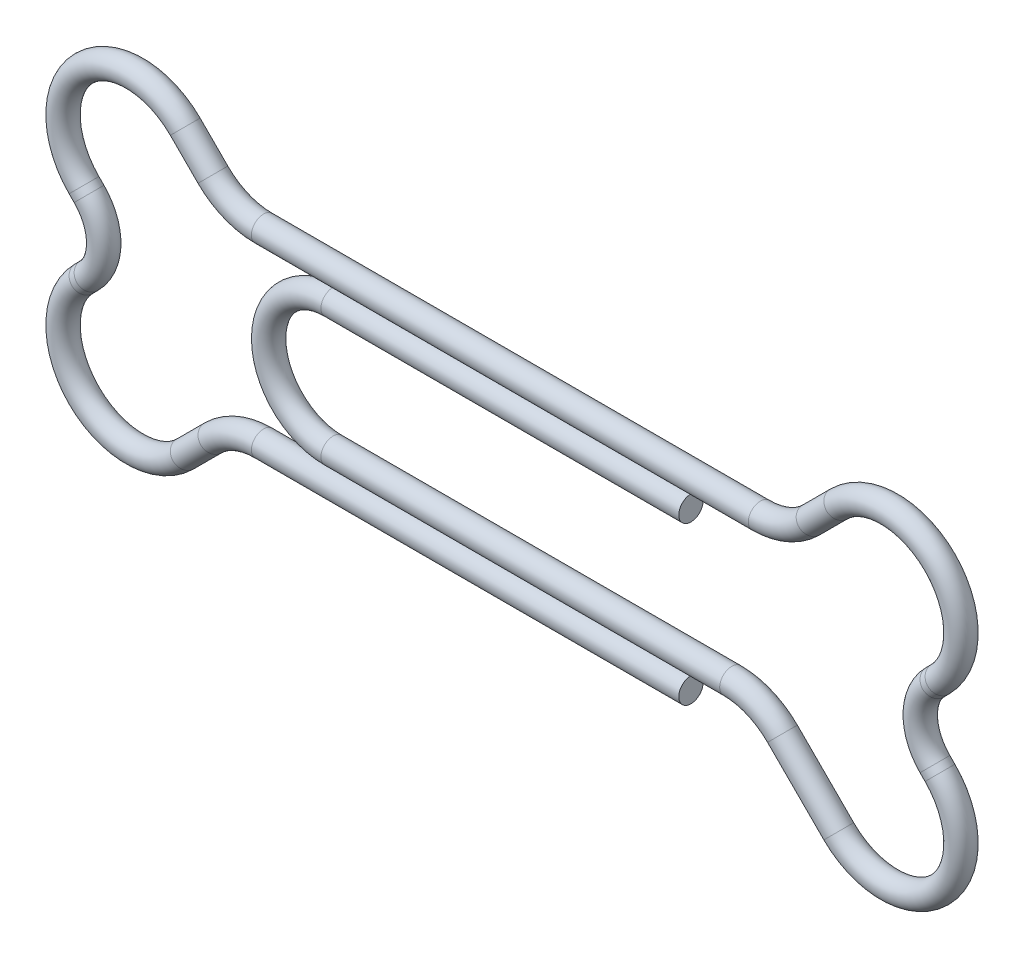
SolidWorks part; units mm, degrees
ref_plane "Спереди" through (0, 0, 0) normal (0, 0, 1) x (1, 0, 0)
ref_plane "Сверху" through (0, 0, 0) normal (0, 1, 0) x (1, 0, 0)
ref_plane "Справа" through (0, 0, 0) normal (1, 0, 0) x (0, 0, -1)
sketch "Эскиз1" plane through (0, 0, 0) normal (0, 0, 1) x (1, 0, 0)
  line L0 (0, 0) -> (25, 0) construction
  line L1 (0, 4.5) -> (25, 4.5) construction
  line L2 (0, -4.5) -> (25, -4.5) construction
  line L3 (-7.5, 0) -> (32.5, 0) construction
  line L4 (-7.5, 6.5) -> (32.5, 6.5) construction
  line L5 (-7.5, -6.5) -> (32.5, -6.5) construction
  line L6 (32.5, 0) -> (38.864, 6.364) construction
  line L7 (28.9645, 3.5355) -> (35.3284, 9.8995) construction
  line L8 (36.0355, -3.5355) -> (42.3995, 2.8284) construction
  line L9 (0, 0) -> (-25.7489, 0) construction
  line L10 (32.5, 0) -> (38.864, -6.364) construction
  line L11 (28.9645, -3.5355) -> (35.3284, -9.8995) construction
  line L12 (36.0355, 3.5355) -> (42.3995, -2.8284) construction
  line L13 (12.5, 0) -> (12.5, 10.4926) construction
  line L14 (-7.5, 0) -> (-13.864, -6.364) construction
  line L15 (-3.9645, -3.5355) -> (-10.3284, -9.8995) construction
  line L16 (-11.0355, 3.5355) -> (-17.3995, -2.8284) construction
  line L17 (-7.5, 0) -> (-13.864, 6.364) construction
  line L18 (-3.9645, 3.5355) -> (-10.3284, 9.8995) construction
  line L19 (-11.0355, -3.5355) -> (-17.3995, 2.8284) construction
  line L20 (25, -4.5) -> (29.9289, -4.5) construction
  arc A0 (0, 4.5) -> (0, -4.5) centre (0, 0) ccw construction
  arc A1 (25, -4.5) -> (25, 4.5) centre (25, 0) ccw construction
  arc A2 (-7.5, 6.5) -> (-7.5, -6.5) centre (-7.5, 0) ccw construction
  arc A3 (32.5, -6.5) -> (32.5, 6.5) centre (32.5, 0) ccw construction
  arc A4 (28.9645, 3.5355) -> (36.0355, -3.5355) centre (32.5, 0) ccw construction
  arc A5 (42.3995, 2.8284) -> (35.3284, 9.8995) centre (38.864, 6.364) ccw construction
  arc A6 (28.9645, -3.5355) -> (36.0355, 3.5355) centre (32.5, 0) cw construction
  arc A7 (42.3995, -2.8284) -> (35.3284, -9.8995) centre (38.864, -6.364) cw construction
  arc A8 (-3.9645, -3.5355) -> (-11.0355, 3.5355) centre (-7.5, 0) ccw construction
  arc A9 (-17.3995, -2.8284) -> (-10.3284, -9.8995) centre (-13.864, -6.364) ccw construction
  arc A10 (-3.9645, 3.5355) -> (-11.0355, -3.5355) centre (-7.5, 0) cw construction
  arc A11 (-17.3995, 2.8284) -> (-10.3284, 9.8995) centre (-13.864, 6.364) cw construction
  point P3 (12.5, 0)
  point P10 (12.5, 0)
  point P17 (35.682, 3.182)
  point P26 (35.682, -3.182)
  point P35 (-10.682, -3.182)
  point P42 (-10.682, 3.182)
  dimension "D1" = 25
  dimension "D2" = 9
  dimension "D3" = 13
  dimension "D4" = 40
  dimension "D5" = 45
  dimension "D6" = 9
  dimension "D7" = 10
sketch "Эскиз2" plane through (0, 0, 0) normal (0, 0, 1) x (1, 0, 0)
  line L0 (25, 4.5) -> (0, 4.5)
  line L1 (0, -4.5) -> (25, -4.5)
  line L2 (25, -4.5) -> (27.8579, -4.5)
  line L3 (31.3934, -5.9645) -> (35.3284, -9.8995)
  line L4 (42.3995, -2.8284) -> (42.0459, -2.4749)
  line L5 (36.0355, -3.5355) -> (42.3995, 2.8284) construction
  line L6 (36.0355, 3.5355) -> (42.3995, -2.8284) construction
  line L7 (42.0459, 2.4749) -> (42.3995, 2.8284)
  line L8 (35.3284, 9.8995) -> (33.3934, 7.9645)
  line L9 (-7.5, 6.5) -> (32.5, 6.5) construction
  line L10 (28.9645, 3.5355) -> (35.3284, 9.8995) construction
  line L11 (29.8579, 6.5) -> (-4.8579, 6.5)
  line L12 (-8.3934, 7.9645) -> (-10.3284, 9.8995)
  line L13 (-17.3995, 2.8284) -> (-17.0459, 2.4749)
  line L14 (0, 0) -> (-25.7489, 0) construction
  line L15 (-11.0355, 3.5355) -> (-17.3995, -2.8284) construction
  line L16 (-17.0459, -2.4749) -> (-17.3995, -2.8284)
  line L17 (-10.3284, -9.8995) -> (-8.3934, -7.9645)
  line L18 (-7.5, -6.5) -> (32.5, -6.5) construction
  line L19 (-3.9645, -3.5355) -> (-10.3284, -9.8995) construction
  line L20 (-4.8579, -6.5) -> (25, -6.5)
  arc A0 (0, 4.5) -> (0, -4.5) centre (0, 0) ccw
  arc A1 (35.3284, -9.8995) -> (42.3995, -2.8284) centre (38.864, -6.364) ccw
  arc A2 (42.3995, 2.8284) -> (35.3284, 9.8995) centre (38.864, 6.364) ccw
  arc A3 (-10.3284, 9.8995) -> (-17.3995, 2.8284) centre (-13.864, 6.364) ccw
  arc A4 (-17.3995, -2.8284) -> (-10.3284, -9.8995) centre (-13.864, -6.364) ccw
  arc A5 (-17.0459, -2.4749) -> (-17.0459, 2.4749) centre (-19.5208, 0) ccw
  arc A6 (42.0459, -2.4749) -> (42.0459, 2.4749) centre (44.5208, 0) cw
  arc A7 (33.3934, 7.9645) -> (29.8579, 6.5) centre (29.8579, 11.5) cw
  arc A8 (-4.8579, -6.5) -> (-8.3934, -7.9645) centre (-4.8579, -11.5) ccw
  arc A9 (-8.3934, 7.9645) -> (-4.8579, 6.5) centre (-4.8579, 11.5) ccw
  arc A10 (27.8579, -4.5) -> (31.3934, -5.9645) centre (27.8579, -9.5) cw
  point P54 (-14.5711, 0)
  point P59 (39.5711, 0)
  point P62 (31.9289, 6.5)
  point P65 (-6.9289, -6.5)
  point P68 (-6.9289, 6.5)
  point P71 (29.9289, -4.5)
  dimension "D1" = 3.5
  dimension "D2" = 3.5
  dimension "D3" = 5
  dimension "D4" = 5
ref_plane "Плоскость1" through (25, -6.5, 0) normal (1, 0, 0) x (0, 0, -1)
sketch "Эскиз3" plane through (25, -6.5, 0) normal (1, 0, 0) x (0, 0, -1)
  circle A0 centre (0, 0) radius 0.85
  dimension "D1" = 1.7
sweep "По траектории1" add profiles "Эскиз3" path "Эскиз2"
